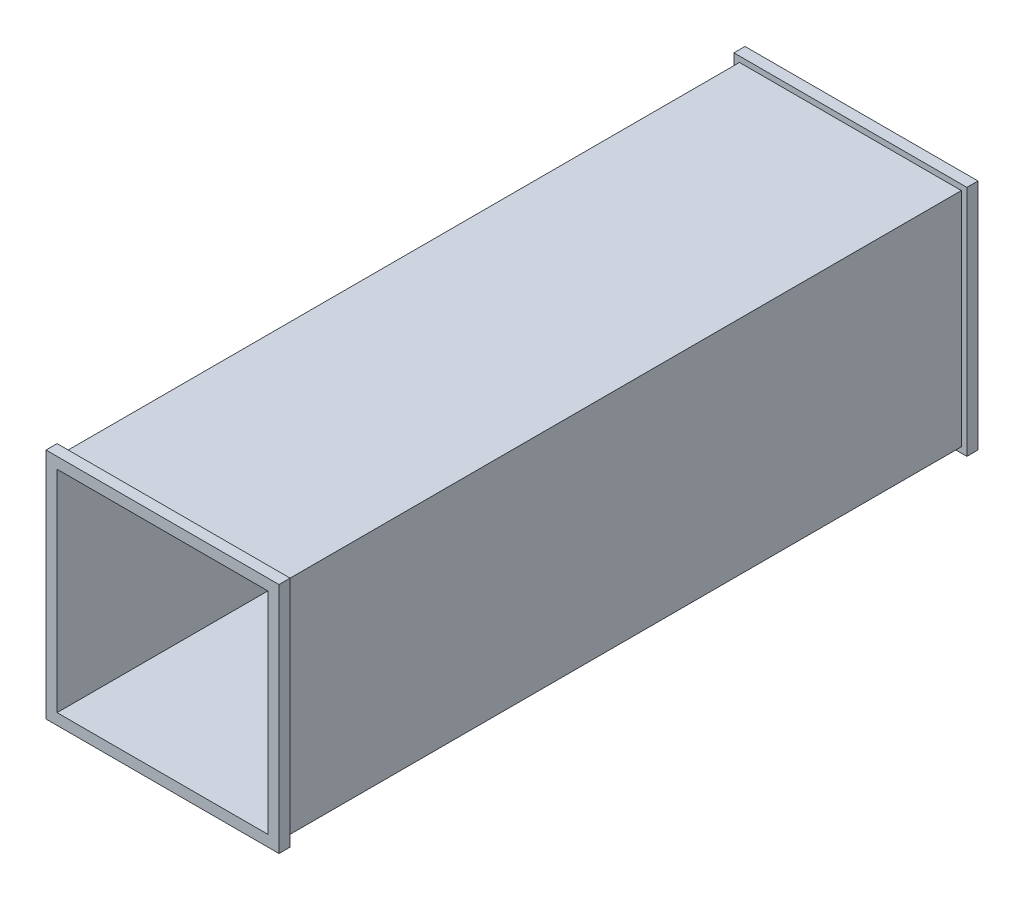
SolidWorks part; units mm, degrees
ref_plane "Front Plane" through (0, 0, 0) normal (0, 0, 1) x (1, 0, 0)
ref_plane "Top Plane" through (0, 0, 0) normal (0, 1, 0) x (1, 0, 0)
ref_plane "Right Plane" through (0, 0, 0) normal (1, 0, 0) x (0, 0, -1)
sketch "Sketch1" plane through (0, 0, 0) normal (0, 0, 1) x (1, 0, 0)
  line L1 (-254, -254) -> (254, -254)
  line L2 (-254, -254) -> (-254, 254)
  line L3 (-254, 254) -> (254, 254)
  line L4 (254, -254) -> (254, 254)
  line L5 (-254, -254) -> (254, 254) construction
  line L6 (-254, 254) -> (254, -254) construction
  point P0 (0, 0)
  dimension "D1" = 508
  dimension "D2" = 508
ref_plane "Plane1" through (0, 0, 1549.4) normal (0, 0, 1) x (1, 0, 0)
sketch "Sketch2" plane through (0, 0, 1549.4) normal (0, 0, 1) x (1, 0, 0)
  line L1 (-254, -254) -> (254, -254)
  line L2 (-254, -254) -> (-254, 254)
  line L3 (-254, 254) -> (254, 254)
  line L4 (254, -254) -> (254, 254)
  line L5 (-254, -254) -> (254, 254) construction
  line L6 (-254, 254) -> (254, -254) construction
  point P0 (0, 0)
loft "Loft1" add profiles "Sketch2", "Sketch1"
sketch "Sketch3" plane through (0, 0, 1549.4) normal (0, 0, 1) x (1, 0, 0)
  line L14 (241.3, -241.3) -> (241.3, 241.3)
  line L15 (-241.3, -241.3) -> (241.3, -241.3)
  line L16 (-241.3, 241.3) -> (-241.3, -241.3)
  line L17 (241.3, 241.3) -> (-241.3, 241.3)
  line L18 (241.3, -241.3) -> (241.3, 241.3)
  line L19 (-241.3, -241.3) -> (241.3, -241.3)
  line L20 (-241.3, 241.3) -> (-241.3, -241.3)
  line L21 (241.3, 241.3) -> (-241.3, 241.3)
  dimension "D1" = 12.7
sketch "Sketch4" plane through (0, 0, 0) normal (0, 0, -1) x (-1, 0, 0)
  line L1 (-241.3, -241.3) -> (241.3, -241.3)
  line L2 (-241.3, -241.3) -> (-241.3, 241.3)
  line L3 (-241.3, 241.3) -> (241.3, 241.3)
  line L4 (241.3, -241.3) -> (241.3, 241.3)
  line L5 (-241.3, -241.3) -> (241.3, 241.3) construction
  line L6 (-241.3, 241.3) -> (241.3, -241.3) construction
  point P0 (0, 0)
loft "Cut-Loft1" cut profiles "Sketch4", "Sketch3"
sketch "Sketch5" plane through (0, 0, 0) normal (0, 0, -1) x (-1, 0, 0)
  line L1 (-241.3, -241.3) -> (241.3, -241.3)
  line L2 (-241.3, -241.3) -> (-241.3, 241.3)
  line L3 (-241.3, 241.3) -> (241.3, 241.3)
  line L4 (241.3, -241.3) -> (241.3, 241.3)
  line L5 (-241.3, -241.3) -> (241.3, 241.3) construction
  line L6 (-241.3, 241.3) -> (241.3, -241.3) construction
  line L20 (266.7, -266.7) -> (266.7, 266.7)
  line L21 (-266.7, -266.7) -> (266.7, -266.7)
  line L22 (-266.7, 266.7) -> (-266.7, -266.7)
  line L23 (266.7, 266.7) -> (-266.7, 266.7)
  line L24 (266.7, -266.7) -> (266.7, 266.7)
  line L25 (-266.7, -266.7) -> (266.7, -266.7)
  line L26 (-266.7, 266.7) -> (-266.7, -266.7)
  line L27 (266.7, 266.7) -> (-266.7, 266.7)
  point P0 (0, 0)
  dimension "D1" = 12.7
extrude "Boss-Extrude1" add sketch "Sketch5" along normal blind 25.4
sketch "Sketch6" plane through (0, 0, 1549.4) normal (0, 0, 1) x (1, 0, 0)
  line L1 (-241.3, -241.3) -> (241.3, -241.3)
  line L2 (-241.3, -241.3) -> (-241.3, 241.3)
  line L3 (-241.3, 241.3) -> (241.3, 241.3)
  line L4 (241.3, -241.3) -> (241.3, 241.3)
  line L5 (-241.3, -241.3) -> (241.3, 241.3) construction
  line L6 (-241.3, 241.3) -> (241.3, -241.3) construction
  line L20 (266.7, -266.7) -> (266.7, 266.7)
  line L21 (-266.7, -266.7) -> (266.7, -266.7)
  line L22 (-266.7, 266.7) -> (-266.7, -266.7)
  line L23 (266.7, 266.7) -> (-266.7, 266.7)
  line L24 (266.7, -266.7) -> (266.7, 266.7)
  line L25 (-266.7, -266.7) -> (266.7, -266.7)
  line L26 (-266.7, 266.7) -> (-266.7, -266.7)
  line L27 (266.7, 266.7) -> (-266.7, 266.7)
  point P0 (0, 0)
  dimension "D1" = 12.7
extrude "Boss-Extrude2" add sketch "Sketch6" along normal blind 25.4
